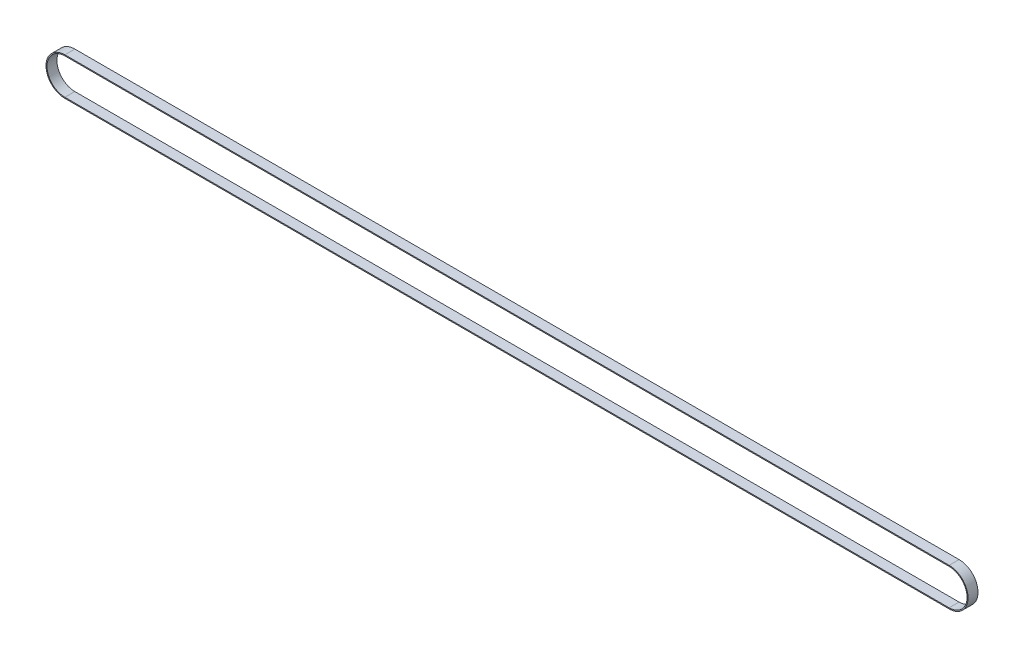
SolidWorks part; units mm, degrees
ref_plane "Front" through (0, 0, 0) normal (0, 0, 1) x (1, 0, 0)
ref_plane "Top" through (0, 0, 0) normal (0, 1, 0) x (1, 0, 0)
ref_plane "Right" through (0, 0, 0) normal (1, 0, 0) x (0, 0, -1)
sketch "草图1" plane through (0, 0, 0) normal (0, 0, 1) x (1, 0, 0)
  line L0 (0, 0) -> (889, 0) construction
  line L1 (0, -19) -> (889, -19)
  line L2 (889, 19) -> (0, 19)
  line L3 (889, 18) -> (0, 18)
  line L4 (0, -18) -> (889, -18)
  arc A0 (0, 18) -> (0, -18) centre (0, 0) ccw
  arc A1 (0, 19) -> (0, -19) centre (0, 0) ccw
  arc A2 (889, -18) -> (889, 18) centre (889, 0) ccw
  arc A3 (889, -19) -> (889, 19) centre (889, 0) ccw
  dimension "D1" = 36
  dimension "D2" = 1
  dimension "D3" = 1
  dimension "D4" = 36
  dimension "D5" = 889
extrude "凸台-拉伸1" add sketch "草图1" along normal blind 10
